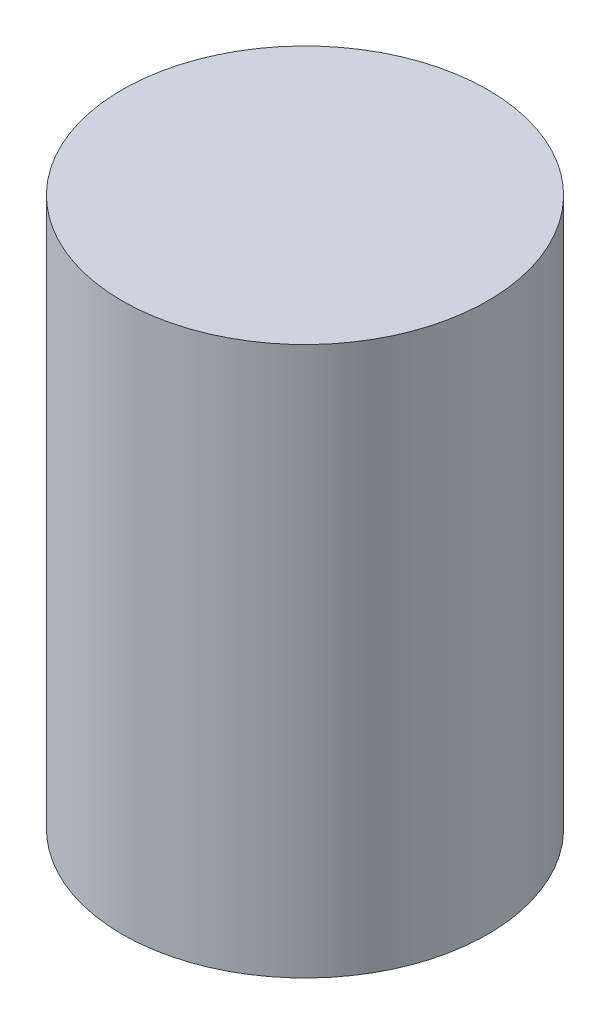
SolidWorks part; units mm, degrees
ref_plane "Front Plane" through (0, 0, 0) normal (0, 0, 1) x (1, 0, 0)
ref_plane "Top Plane" through (0, 0, 0) normal (0, 1, 0) x (1, 0, 0)
ref_plane "Right Plane" through (0, 0, 0) normal (1, 0, 0) x (0, 0, -1)
sketch "Sketch2" plane through (0, 0, 0) normal (0, 1, 0) x (1, 0, 0)
  circle A0 centre (0, 0) radius 2
  dimension "D1" = 4
extrude "Boss-Extrude1" add sketch "Sketch2" along normal blind 6
sketch "Sketch3" plane through (0, 6, 0) normal (0, 1, 0) x (1, 0, 0)
  circle A0 centre (0, 0) radius 2
curve "Helix/Spiral1" pitch 0.5 height 6 turns 12
sketch "Sketch5" plane through (0, 0, 0) normal (0, 0, 1) x (1, 0, 0)
  line L0 (2, 6) -> (-2, 6) construction
  line L1 (0.4, 0) -> (2.8, -1.3856)
  line L2 (2.8, -1.3856) -> (2.8, 1.3856)
  line L3 (2.8, 1.3856) -> (0.4, 0)
  line L4 (-2, 6) -> (-2, 0) construction
  circle A0 centre (2, 0) radius 0.8 construction
  dimension "D3" = 1.6
  dimension "D1" = 6
  dimension "D2" = 4
